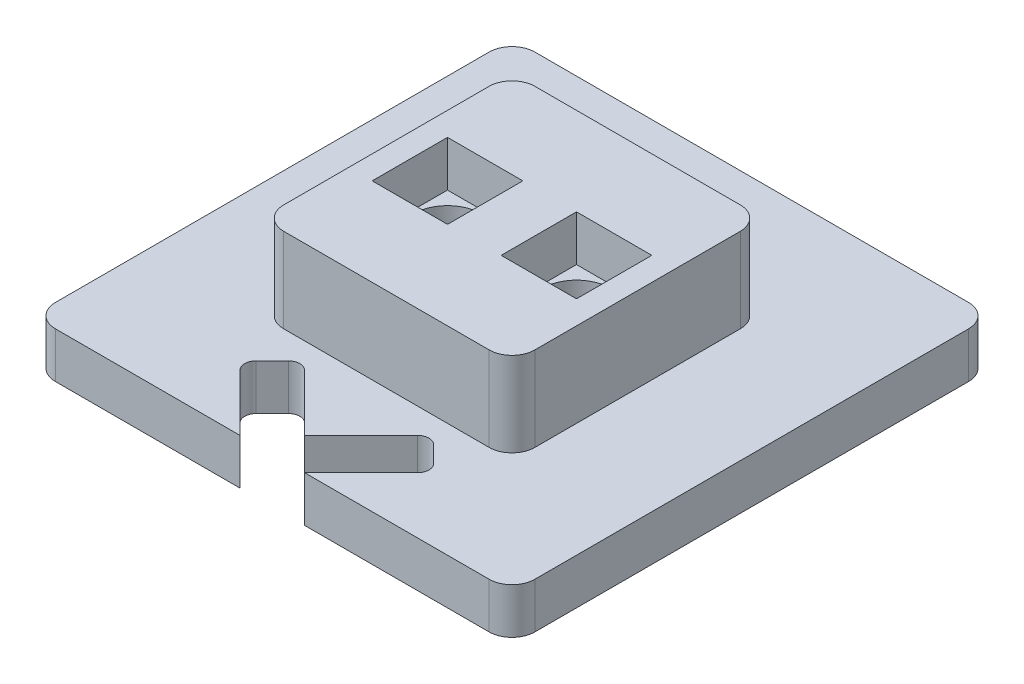
SolidWorks part; units mm, degrees
ref_plane "Front Plane" through (0, 0, 0) normal (0, 0, 1) x (1, 0, 0)
ref_plane "Top Plane" through (0, 0, 0) normal (0, 1, 0) x (1, 0, 0)
ref_plane "Right Plane" through (0, 0, 0) normal (1, 0, 0) x (0, 0, -1)
sketch "Sketch1" plane through (0, 0, 0) normal (0, 1, 0) x (1, 0, 0)
  line L1 (-5.5, -5.5) -> (5.5, -5.5)
  line L2 (-5.5, -5.5) -> (-5.5, 5.5)
  line L3 (-5.5, 5.5) -> (5.5, 5.5)
  line L4 (5.5, -5.5) -> (5.5, 5.5)
  line L5 (-5.5, -5.5) -> (5.5, 5.5) construction
  line L6 (-5.5, 5.5) -> (5.5, -5.5) construction
  point P0 (0, 0)
  dimension "D1" = 11
  dimension "D2" = 11
extrude "Boss-Extrude1" add sketch "Sketch1" along normal blind 3.7
fillet "Fillet1" radius 1 4 edges at (-5.5, 1.85, -5.5) (-5.5, 1.85, 5.5) (5.5, 1.85, -5.5) (5.5, 1.85, 5.5)
sketch "Sketch2" plane through (0, 3.7, 0) normal (0, 1, 0) x (1, 0, 0)
  line L0 (-2.825, 0) -> (2.825, 0) construction
  line L2 (-4.475, -1.65) -> (-1.175, -1.65)
  line L3 (-4.475, -1.65) -> (-4.475, 1.65)
  line L4 (-4.475, 1.65) -> (-1.175, 1.65)
  line L5 (-1.175, -1.65) -> (-1.175, 1.65)
  line L6 (-4.475, -1.65) -> (-1.175, 1.65) construction
  line L7 (-4.475, 1.65) -> (-1.175, -1.65) construction
  line L8 (1.175, -1.65) -> (4.475, -1.65)
  line L9 (1.175, -1.65) -> (1.175, 1.65)
  line L10 (1.175, 1.65) -> (4.475, 1.65)
  line L11 (4.475, -1.65) -> (4.475, 1.65)
  line L12 (1.175, -1.65) -> (4.475, 1.65) construction
  line L13 (1.175, 1.65) -> (4.475, -1.65) construction
  point P4 (0, 0)
  dimension "D1" = 3.3
  dimension "D2" = 3.3
  dimension "D3" = 3.3
  dimension "D4" = 3.3
  dimension "D5" = 5.65
extrude "Cut-Extrude1" cut sketch "Sketch2" against normal blind 2
sketch "Sketch4" plane through (0, 0, 0) normal (0, -1, 0) x (-1, 0, 0)
  line L0 (2.825, 0) -> (-2.825, 0) construction
  circle A0 centre (2.825, 0) radius 2.2
  circle A1 centre (-2.825, 0) radius 2.2
  point P4 (0, 0)
  point P8 (0, 0)
  dimension "D1" = 5.65
  dimension "D2" = 4.4
  dimension "D3" = 4.4
extrude "Boss-Extrude2" add sketch "Sketch4" along normal blind 2
sketch "Sketch5" plane through (0, -2, 0) normal (0, -1, 0) x (-1, 0, 0)
  line L1 (9.5, 10.5) -> (-9.5, 10.5)
  line L2 (10.5, 9.5) -> (10.5, -9.5)
  line L3 (9.5, -10.5) -> (-9.5, -10.5)
  line L4 (-10.5, 9.5) -> (-10.5, -9.5)
  line L5 (10.5, 10.5) -> (-10.5, -10.5) construction
  line L6 (10.5, -10.5) -> (-10.5, 10.5) construction
  arc A0 (10.5, -9.5) -> (9.5, -10.5) centre (9.5, -9.5) cw
  arc A1 (-10.5, -9.5) -> (-9.5, -10.5) centre (-9.5, -9.5) ccw
  arc A2 (-9.5, 10.5) -> (-10.5, 9.5) centre (-9.5, 9.5) ccw
  arc A3 (9.5, 10.5) -> (10.5, 9.5) centre (9.5, 9.5) cw
  point P0 (0, 0)
  dimension "D3" = 1
  dimension "D1" = 21
  dimension "D2" = 21
extrude "Boss-Extrude3" add sketch "Sketch5" against normal blind 2
sketch "Sketch3" plane through (0, 3.7, 0) normal (0, 1, 0) x (1, 0, 0)
  line L0 (-2.825, 0) -> (2.825, 0) construction
  circle A0 centre (-2.825, 0) radius 1.5
  circle A1 centre (2.825, 0) radius 1.5
  point P4 (0, 0)
  point P5 (0, 0)
  point P8 (0, 0)
  dimension "D2" = 3
  dimension "D3" = 3
  dimension "D1" = 5.65
extrude "Cut-Extrude2" cut sketch "Sketch3" against normal through all
sketch "Sketch7" plane through (0, 0, 0) normal (0, 1, 0) x (1, 0, 0)
  line L0 (9.5, -10.5) -> (-9.5, -10.5) construction
  line L1 (2.8284, -14.7426) -> (4.2426, -13.3284)
  line L2 (2.8284, -14.7426) -> (-3.8891, -8.0251)
  line L3 (-3.8891, -7.318) -> (-3.182, -6.6109)
  line L4 (4.2426, -13.3284) -> (-2.4749, -6.6109)
  line L5 (2.8284, -14.7426) -> (-2.8284, -6.2574) construction
  line L6 (-4.2426, -7.6716) -> (4.2426, -13.3284) construction
  line L8 (-4.2426, -13.3284) -> (-2.8284, -14.7426)
  line L9 (-4.2426, -13.3284) -> (2.4749, -6.6109)
  line L10 (3.182, -6.6109) -> (3.8891, -7.318)
  line L11 (-2.8284, -14.7426) -> (3.8891, -8.0251)
  line L12 (-4.2426, -13.3284) -> (4.2426, -7.6716) construction
  line L13 (2.8284, -6.2574) -> (-2.8284, -14.7426) construction
  arc A0 (-2.4749, -6.6109) -> (-3.182, -6.6109) centre (-2.8284, -6.9645) ccw
  arc A1 (3.8891, -7.318) -> (3.8891, -8.0251) centre (3.5355, -7.6716) cw
  arc A2 (3.182, -6.6109) -> (2.4749, -6.6109) centre (2.8284, -6.9645) ccw
  arc A3 (-3.8891, -7.318) -> (-3.8891, -8.0251) centre (-3.5355, -7.6716) ccw
  point P0 (0, -10.5)
  point P7 (0, -10.5)
  point P12 (-1.4142, -10.5)
  point P13 (1.4142, -10.5)
  line M12 (-9.5, -10.5) -> (9.5, -10.5)
  dimension "D7" = 0.5
  dimension "D8" = 0.5
  dimension "D1" = 2
  dimension "D2" = 45
  dimension "D3" = 2
  dimension "D4" = 45
  dimension "D5" = 4
  dimension "D6" = 4
extrude "Cut-Extrude3" cut sketch "Sketch7" against normal through all contours L10 A2 L9 L4 L11 A1 | L3 A3 L2 L9 L4 A0 | L9 L4 M12
equation "\"D2@Sketch2\"=\"D1@Sketch2\""
equation "\"D3@Sketch2\"=\"D1@Sketch2\""
equation "\"D4@Sketch2\"=\"D1@Sketch2\""
equation "\"D2@Sketch1\"=\"D1@Sketch1\""
equation "\"D3@Sketch3\"=\"D2@Sketch3\""
equation "\"D3@Sketch4\"=\"D2@Sketch4\""
equation "\"D2@Sketch5\"=\"D1@Sketch5\""
equation "\"D3@Sketch7\"=\"D1@Sketch7\""
equation "\"D6@Sketch7\"=\"D5@Sketch7\""
